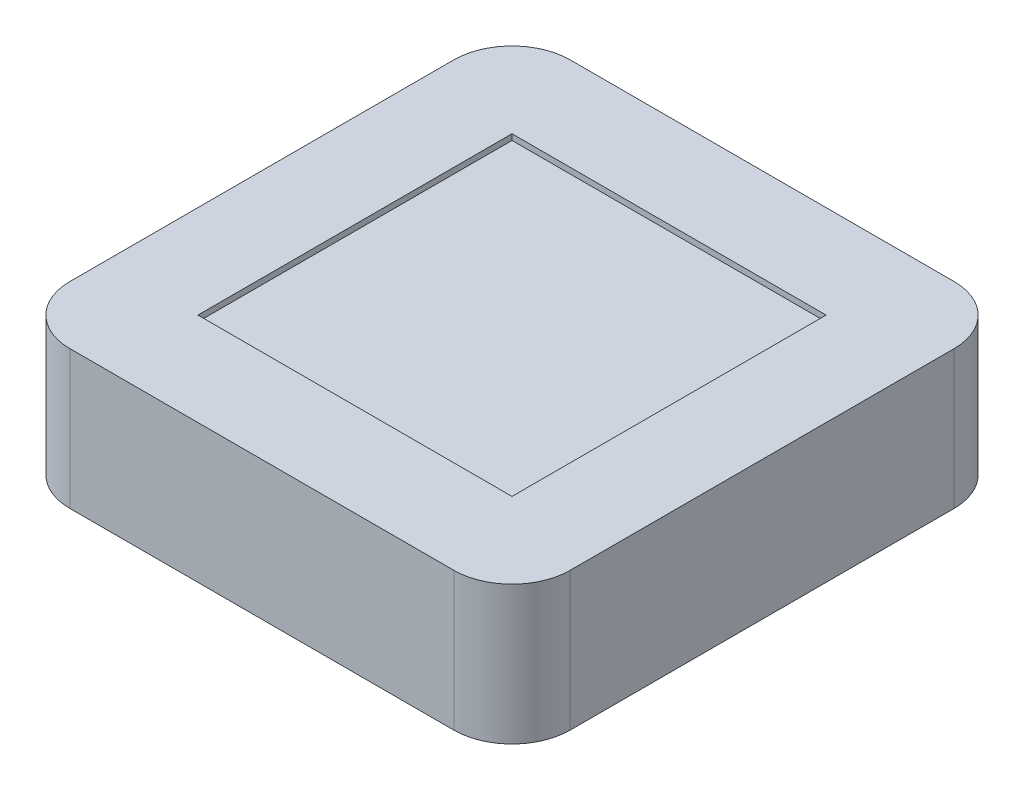
SolidWorks part; units mm, degrees
ref_plane "Alzado" through (0, 0, 0) normal (0, 0, 1) x (1, 0, 0)
ref_plane "Planta" through (0, 0, 0) normal (0, 1, 0) x (1, 0, 0)
ref_plane "Vista lateral" through (0, 0, 0) normal (1, 0, 0) x (0, 0, -1)
sketch "Croquis1" plane through (0, 0, 0) normal (0, 1, 0) x (1, 0, 0)
  line L1 (0, 0) -> (43, 0)
  line L2 (0, 0) -> (0, 43)
  line L3 (0, 43) -> (43, 43)
  line L4 (43, 0) -> (43, 43)
  dimension "D1" = 43
  dimension "D2" = 43
extrude "Saliente-Extruir1" add sketch "Croquis1" along normal blind 11.9
sketch "Croquis2" plane through (0, 11.9, 0) normal (0, 1, 0) x (1, 0, 0)
  line L0 (0, 0) -> (43, 43) construction
  line L2 (8, 8) -> (35, 8)
  line L3 (8, 8) -> (8, 35)
  line L4 (8, 35) -> (35, 35)
  line L5 (35, 8) -> (35, 35)
  line L6 (8, 8) -> (35, 35) construction
  line L7 (8, 35) -> (35, 8) construction
  point P4 (21.5, 21.5)
  dimension "D1" = 27
extrude "Cortar-Extruir1" cut sketch "Croquis2" against normal blind 0.5
fillet "Redondeo1" radius 5 4 edges at (43, 5.95, 0) (43, 5.95, -43) (0, 5.95, 0) (0, 5.95, -43)
